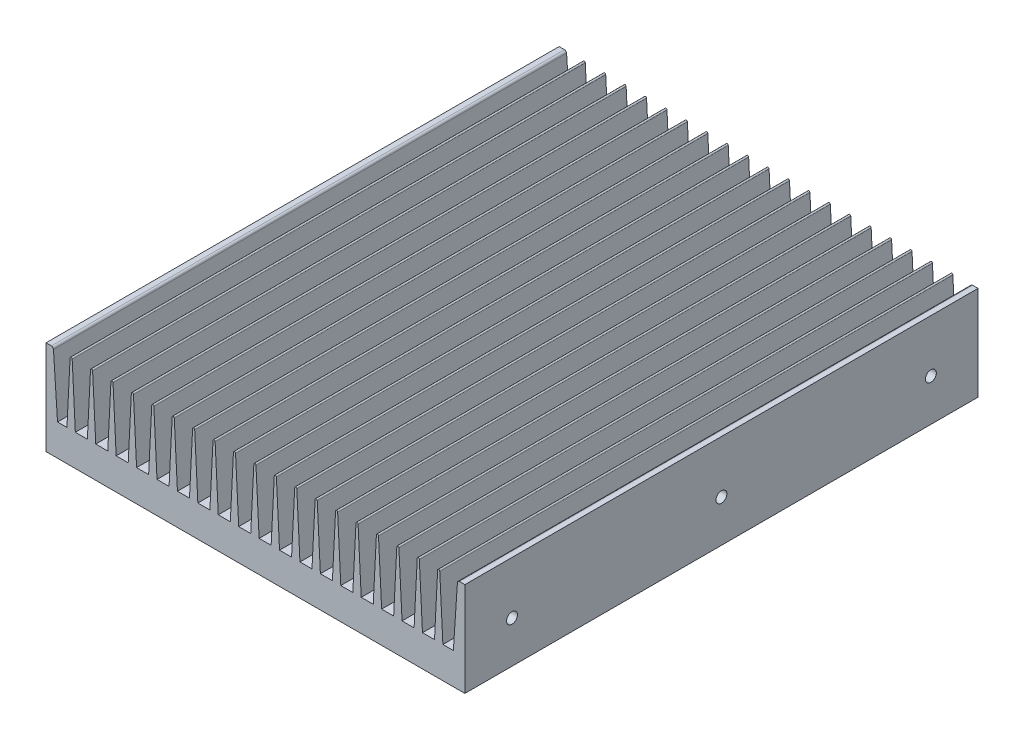
SolidWorks part; units mm, degrees
ref_plane "Спереди" through (0, 0, 0) normal (0, 0, 1) x (1, 0, 0)
ref_plane "Сверху" through (0, 0, 0) normal (0, 1, 0) x (1, 0, 0)
ref_plane "Справа" through (0, 0, 0) normal (1, 0, 0) x (0, 0, -1)
sketch "Эскиз1" plane through (0, 0, 0) normal (0, 0, 1) x (1, 0, 0)
  line L0 (0, 45) -> (2.5644, 45)
  line L1 (0, 0) -> (200, 0)
  line L2 (3.5622, 44.0665) -> (5.5, 15)
  line L3 (0, 45) -> (0, 0)
  line L4 (200, 45) -> (200, 0)
  line L5 (100, 63.7127) -> (100, -22.2582) construction
  line L8 (200, 45) -> (197.4356, 45)
  line L9 (196.4378, 44.0665) -> (194.5, 15)
  line L10 (5.5, 15) -> (194.5, 15)
  arc A0 (2.5644, 45) -> (3.5622, 44.0665) centre (2.5644, 44) cw
  arc A2 (197.4356, 45) -> (196.4378, 44.0665) centre (197.4356, 44) ccw
  point P18 (196.5, 45)
  dimension "D9" = 1
  dimension "D1" = 200
  dimension "D2" = 15
  dimension "D3" = 45
  dimension "D4" = 5.5
  dimension "D7" = 3.5
extrude "Вытянуть1" add sketch "Эскиз1" along normal blind 245
sketch "Эскиз2" plane through (0, 0, 245) normal (0, 0, 1) x (1, 0, 0)
  line L0 (194.5, 15) -> (5.5, 15) construction
  line L1 (11.5, 44.5) -> (10, 15)
  line L2 (12, 44.5) -> (12, 22.5548) construction
  line L3 (12.5, 44.5) -> (14, 15)
  line L4 (10, 15) -> (14, 15)
  line L6 (0, 45) -> (0, 0) construction
  arc A0 (11.5, 44.5) -> (12.5, 44.5) centre (12, 44.5) cw
  dimension "D1" = 30
  dimension "D3" = 0.5
  dimension "D2" = 4
  dimension "D4" = 12
  dimension "D5" = 1
extrude "Вытянуть3" add sketch "Эскиз2" against normal blind 245
pattern_curve "Кривая1" of "Вытянуть3" along edge at (100, 0, 0) parameters "D1"=19, "D3"=9.75, "D2"=1, "D4"=50
sketch "Эскиз7" plane through (0, 0, 0) normal (-1, 0, 0) x (0, 0, 1)
  line L0 (-24.1676, 20) -> (275.3481, 20) construction
  line L1 (122.5, 109.9776) -> (122.5, -31.6981) construction
  line L2 (245, 45) -> (245, 0) construction
  line L3 (0, 45) -> (0, 0) construction
  line L4 (245, 0) -> (0, 0) construction
  circle A0 centre (22.5, 20) radius 2.6
  circle A1 centre (222.5, 20) radius 2.6
  circle A2 centre (122.5, 20) radius 2.6
  dimension "D2" = 5.2
  dimension "D3" = 200
  dimension "D1" = 20
extrude "Вырез-Вытянуть4" cut sketch "Эскиз7" against normal blind 6
cosmetic thread "Условное изображение резьбы17" parameters "D1"=5.26, "D2"=6
cosmetic thread "Условное изображение резьбы18" parameters "D1"=5.26, "D2"=6
cosmetic thread "Условное изображение резьбы19" parameters "D1"=5.26, "D2"=6
cosmetic thread "Условное изображение резьбы37"
cosmetic thread "Условное изображение резьбы38"
cosmetic thread "Условное изображение резьбы39"
sketch "Эскиз13" plane through (200, 0, 0) normal (1, 0, 0) x (0, 0, -1)
  circle A0 centre (-222.5, 20) radius 2.6 construction
  circle A1 centre (-222.5, 20) radius 2.6
  circle A2 centre (-122.5, 20) radius 2.6 construction
  circle A3 centre (-122.5, 20) radius 2.6
  circle A4 centre (-22.5, 20) radius 2.6 construction
  circle A5 centre (-22.5, 20) radius 2.6
extrude "Вырез-Вытянуть9" cut sketch "Эскиз13" against normal blind 8
cosmetic thread "Условное изображение резьбы34"
cosmetic thread "Условное изображение резьбы35"
cosmetic thread "Условное изображение резьбы36"
sketch "Эскиз15" plane through (0, 0, 0) normal (0, -1, 0) x (1, 0, 0)
  line L0 (0, 245) -> (200, 245) construction
  line L1 (0, 245) -> (0, 0) construction
  line L2 (25, 220) -> (177.8936, 220) construction
  line L3 (25, 220) -> (25, 215.537) construction
  line L4 (175, 220) -> (175, 110) construction
  line L10 (55, 182) -> (55, 148.5) construction
  circle A0 centre (25, 220) radius 1.6
  circle A1 centre (175, 220) radius 1.6
  circle A2 centre (175, 110) radius 1.6
  circle A3 centre (25, 110) radius 1.6
  circle A4 centre (55, 182) radius 1.3
  circle A5 centre (55, 148.5) radius 1.3
  circle A18 centre (93, 195) radius 2.6
  dimension "D2" = 25
  dimension "D3" = 3.2
  dimension "D4" = 150
  dimension "D5" = 110
  dimension "D6" = 25
  dimension "D7" = 150
  dimension "D8" = 150
  dimension "D10" = 38
  dimension "D11" = 33.5
  dimension "D12" = 2.6
  dimension "D30" = 110
  dimension "D31" = 5.2
  dimension "D32" = 25
  dimension "D33" = 82
  dimension "D9" = 30
extrude "Вырез-Вытянуть10" cut sketch "Эскиз15" against normal blind 10
cosmetic thread "Условное изображение резьбы40" parameters "D1"=8, "D2"=6
cosmetic thread "Условное изображение резьбы41" parameters "D1"=8, "D2"=3
cosmetic thread "Условное изображение резьбы42" parameters "D1"=8, "D2"=3
cosmetic thread "Условное изображение резьбы43" parameters "D1"=8, "D2"=4
cosmetic thread "Условное изображение резьбы44" parameters "D1"=8, "D2"=4
cosmetic thread "Условное изображение резьбы45" parameters "D1"=8, "D2"=4
cosmetic thread "Условное изображение резьбы46" parameters "D1"=8, "D2"=4
